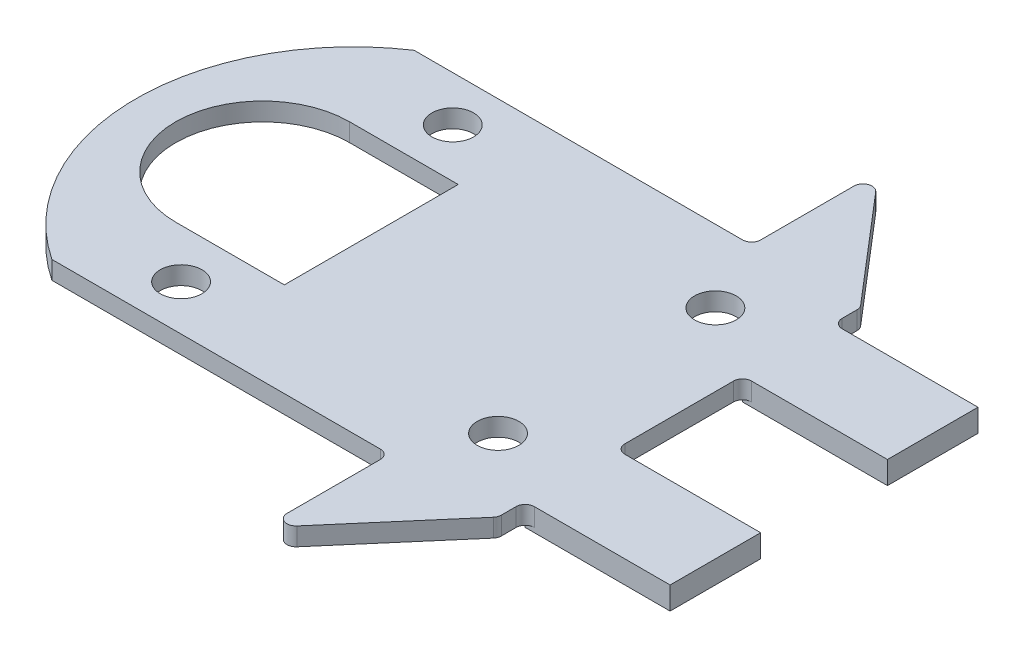
SolidWorks part; units mm, degrees
material "6061 Alloy"
ref_plane "Front Plane" through (0, 0, 0) normal (0, 0, 1) x (1, 0, 0)
ref_plane "Top Plane" through (0, 0, 0) normal (0, 1, 0) x (1, 0, 0)
ref_plane "Right Plane" through (0, 0, 0) normal (1, 0, 0) x (0, 0, -1)
sketch "Sketch2" plane through (0, 0, 0) normal (0, 1, 0) x (1, 0, 0)
  line L1 (15, -10) -> (-9.6332, -10)
  line L2 (15, -10) -> (15, 10)
  line L3 (15, 10) -> (-9.6332, 10)
  line L5 (15, -10) -> (-11.9651, 7.9767) construction
  line L6 (15, 10) -> (-11.9651, -7.9767) construction
  arc A0 (-9.6332, -10) -> (-9.6332, 10) centre (-3, 0) cw
  point P0 (0, 0)
  dimension "D3" = 12
  dimension "D1" = 20
  dimension "D2" = 3
  dimension "D4" = 15
extrude "Boss-Extrude1" add sketch "Sketch2" along normal blind 1
sketch "Sketch3" plane through (0, 1, 0) normal (0, 1, 0) x (1, 0, 0)
  line L0 (-8, 4.8) -> (-2, 4.8)
  line L1 (-2, 4.8) -> (-2, -4.8)
  line L2 (-2, -4.8) -> (-8, -4.8)
  arc A0 (-8, 4.8) -> (-8, -4.8) centre (-8, 0) ccw
  dimension "D1" = 9.6
  dimension "D2" = 8
  dimension "D3" = 6
extrude "Cut-Extrude1" cut sketch "Sketch3" against normal blind 1.25
sketch "Sketch4" plane through (0, 1, 0) normal (0, 1, 0) x (1, 0, 0)
  line L0 (9, 10) -> (9, 17)
  line L1 (15, 10) -> (-9.6332, 10) construction
  line L2 (9, 17) -> (15, 10)
  line L3 (15, 10) -> (9, 10)
  dimension "D1" = 7
  dimension "D2" = 6
extrude "Boss-Extrude2" add sketch "Sketch4" against normal blind 1
fillet "Fillet1" radius 0.5 1 edges at (9, 0.5, -17)
fillet "Fillet2" radius 0.5 1 edges at (9, 0.5, -10)
sketch "Sketch5" plane through (0, 1, 0) normal (0, 1, 0) x (1, 0, 0)
  line L0 (15, -10) -> (15, 10) construction
  line L1 (15, 8.5) -> (23, 8.5)
  line L2 (15, 8.5) -> (15, 3.5)
  line L3 (15, 3.5) -> (23, 3.5)
  line L4 (23, 8.5) -> (23, 3.5)
  line L5 (8.5, 10) -> (-9.6332, 10) construction
  dimension "D1" = 1.5
  dimension "D2" = 5
  dimension "D3" = 8
extrude "Boss-Extrude3" add sketch "Sketch5" against normal blind 1.25
fillet "Fillet3" radius 0.5 3 edges at (15, 0.5, -3.5) (15, 0.5, -8.5) (15, 0.5, -10)
mirror "Mirror6" about plane through (0, 0, 0) normal (0, 0, 1) of "Boss-Extrude3", "Boss-Extrude2", "Fillet1"
fillet "Fillet4" radius 0.5 4 edges at (15, 0.5, 3.5) (15, 0.5, 8.5) (15, 0.5, 10) (9, 0.5, 10)
sketch "Sketch6" plane through (0, 0, 0) normal (0, -1, 0) x (1, 0, 0)
  circle A0 centre (-5, -7.5) radius 1.15
  circle A1 centre (11, -6) radius 1.15
  circle A2 centre (11, 6) radius 1.15
  circle A3 centre (-5, 7.5) radius 1.15
extrude "Cut-Extrude2" cut sketch "Sketch6" against normal through all
sketch "Sketch7" plane through (0, 1, 0) normal (0, 1, 0) x (1, 0, 0)
  point P0 (15.5, 6)
  point P1 (15.5, -6)
